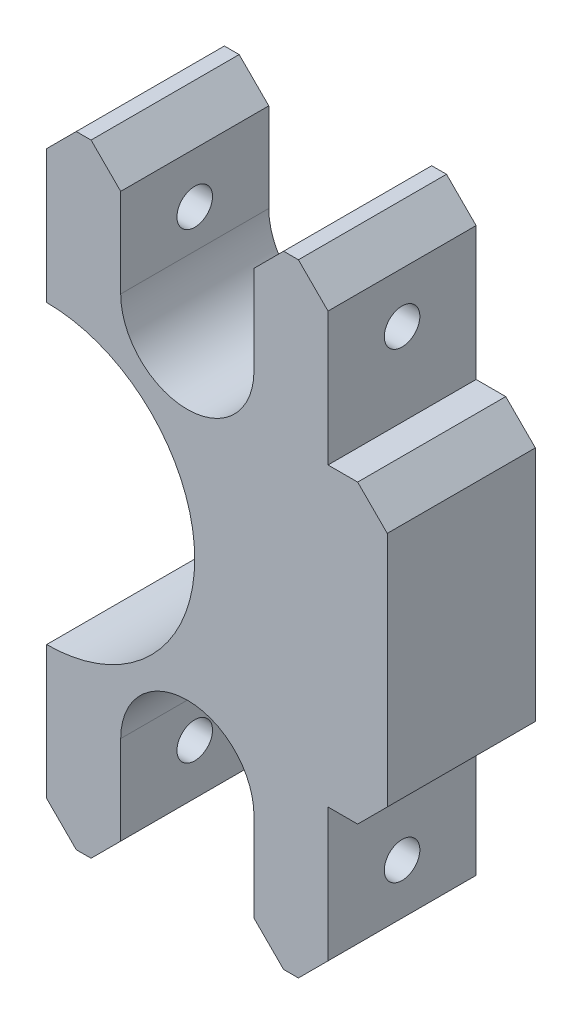
SolidWorks part; units mm, degrees
ref_plane "Front Plane" through (0, 0, 0) normal (0, 0, 1) x (1, 0, 0)
ref_plane "Top Plane" through (0, 0, 0) normal (0, 1, 0) x (1, 0, 0)
ref_plane "Right Plane" through (0, 0, 0) normal (1, 0, 0) x (0, 0, -1)
sketch "Sketch1" plane through (0, 0, 0) normal (0, 0, 1) x (1, 0, 0)
  line L0 (0, 50) -> (0, 105)
  line L1 (0, 105) -> (25, 105)
  line L2 (25, 105) -> (25, 65)
  line L3 (25, 65) -> (70, 65)
  line L4 (70, 65) -> (70, 105)
  line L5 (70, 105) -> (95, 105)
  line L6 (95, 105) -> (95, 50)
  line L7 (95, 50) -> (115, 50)
  line L8 (115, 50) -> (115, -50)
  line L9 (0, 0) -> (226.937, 0) construction
  line L10 (95, -50) -> (115, -50)
  line L11 (95, -105) -> (95, -50)
  line L12 (70, -105) -> (95, -105)
  line L13 (70, -65) -> (70, -105)
  line L14 (25, -65) -> (70, -65)
  line L15 (25, -105) -> (25, -65)
  line L16 (0, -105) -> (25, -105)
  line L17 (0, -50) -> (0, -105)
  arc A0 (0, 50) -> (0, -50) centre (0, 0) cw
  point P15 (115, 0)
  dimension "D1" = 50
  dimension "D2" = 55
  dimension "D3" = 25
  dimension "D4" = 40
  dimension "D5" = 45
  dimension "D6" = 25
  dimension "D7" = 20
  dimension "D8" = 55
extrude "Boss-Extrude1" add sketch "Sketch1" along normal mid plane 50
sketch "Sketch3" plane through (0, 0, 25) normal (0, 0, 1) x (1, 0, 0)
  line L0 (25, 65) -> (70, 65)
  line L1 (0, 0) -> (147.354, 0) construction
  line L2 (25, -65) -> (70, -65)
  arc A0 (70, 65) -> (25, 65) centre (47.5, 65) cw
  arc A1 (70, -65) -> (25, -65) centre (47.5, -65) ccw
extrude "Cut-Extrude1" cut sketch "Sketch3" against normal blind 50
sketch "Sketch4" plane through (0, 0, 0) normal (-1, 0, 0) x (0, 0, 1)
  line L0 (0, 0) -> (145.0443, 0) construction
  circle A0 centre (0, 78) radius 6
  circle A1 centre (0, -78) radius 6
  dimension "D1" = 12
  dimension "D2" = 78
extrude "Cut-Extrude2" cut sketch "Sketch4" against normal blind 200
chamfer "Chamfer1" distance 10 angle 45 2 edges at (115, -50, 0) (115, 50, 0)
chamfer "Chamfer2" distance 10 angle 45 8 edges at (95, -105, 0) (70, -105, 0) (25, -105, 0) (0, -105, 0) (25, 105, 0) (0, 105, 0) (70, 105, 0) (95, 105, 0)
